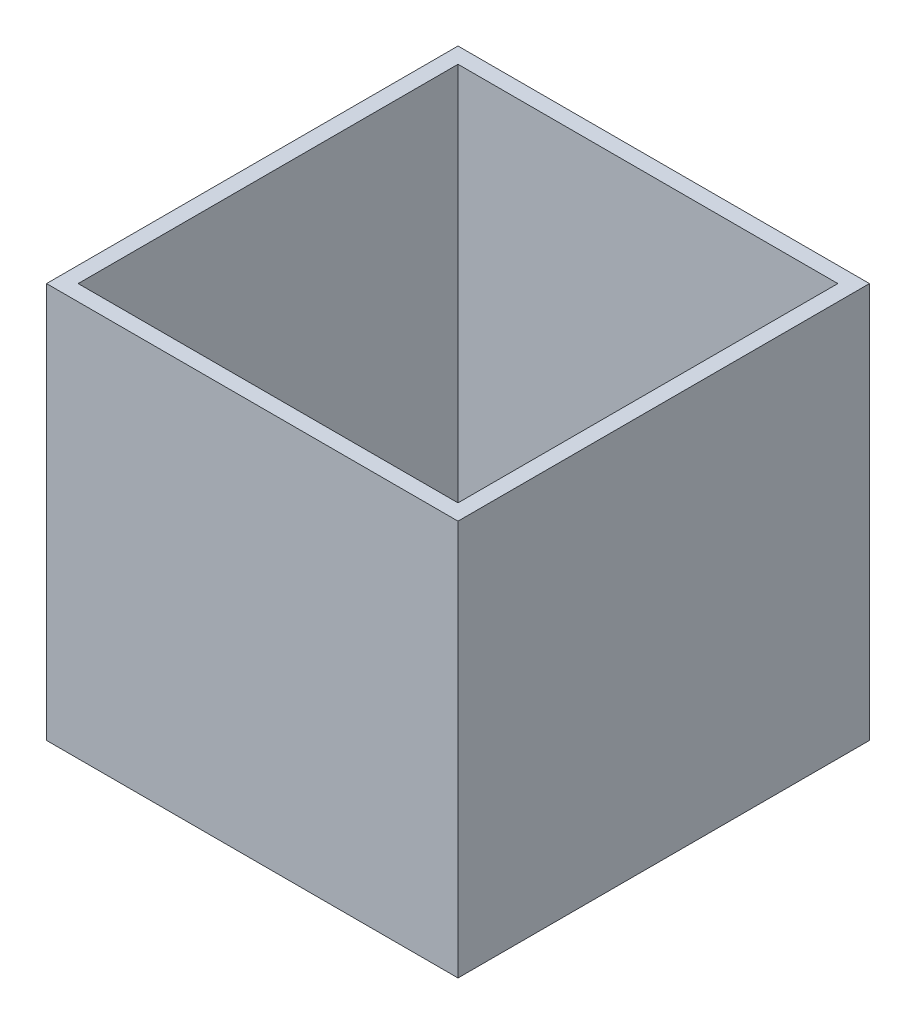
SolidWorks part; units mm, degrees
ref_plane "Front Plane" through (0, 0, 0) normal (0, 0, 1) x (1, 0, 0)
ref_plane "Top Plane" through (0, 0, 0) normal (0, 1, 0) x (1, 0, 0)
ref_plane "Right Plane" through (0, 0, 0) normal (1, 0, 0) x (0, 0, -1)
sketch "Sketch1" plane through (0, 0, 0) normal (0, 1, 0) x (1, 0, 0)
  line L1 (0, 0) -> (330.2, 0)
  line L2 (0, 0) -> (0, 330.2)
  line L3 (0, 330.2) -> (330.2, 330.2)
  line L4 (330.2, 0) -> (330.2, 330.2)
  dimension "D1" = 330.2
  dimension "D2" = 330.2
extrude "Boss-Extrude1" add sketch "Sketch1" along normal blind 317.5
shell "Shell1" thickness 12.7
